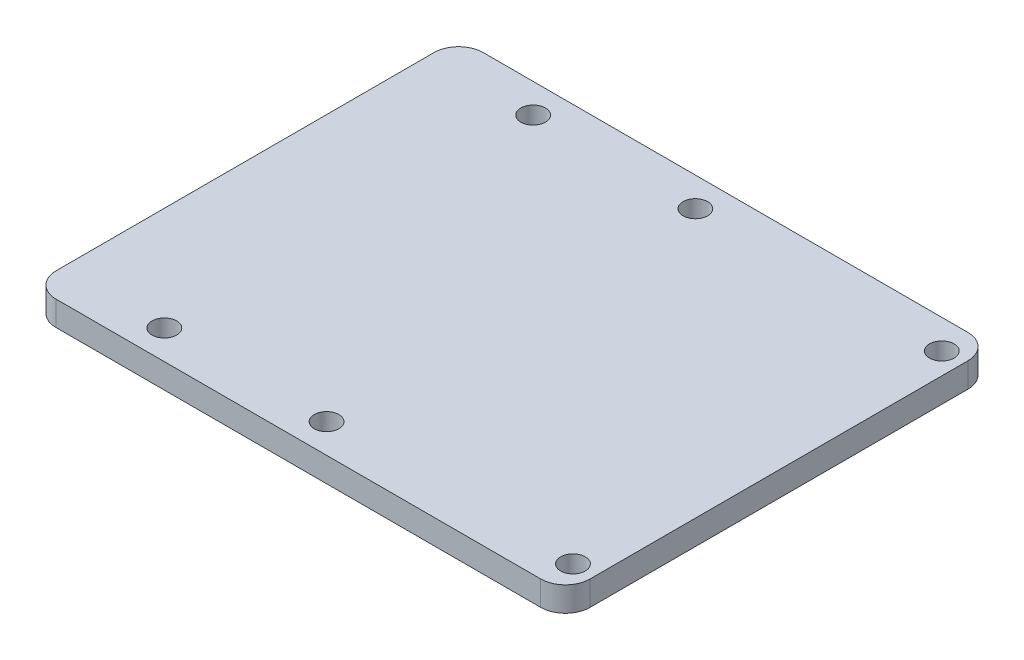
SolidWorks part; units mm, degrees
ref_plane "Front Plane" through (0, 0, 0) normal (0, 0, 1) x (1, 0, 0)
ref_plane "Top Plane" through (0, 0, 0) normal (0, 1, 0) x (1, 0, 0)
ref_plane "Right Plane" through (0, 0, 0) normal (1, 0, 0) x (0, 0, -1)
sketch "Sketch2" plane through (0, 0, 0) normal (0, 1, 0) x (1, 0, 0)
  line L1 (-37.5, -26) -> (27.5, -26)
  line L2 (-37.5, -26) -> (-37.5, 26)
  line L3 (-37.5, 26) -> (27.5, 26)
  line L4 (27.5, -26) -> (27.5, 26)
  line L5 (0, 27) -> (0, -27) construction
  line L6 (-32.5, 0) -> (32.5, 0) construction
  line L7 (-24.875, -22.45) -> (24.875, -22.45)
  line L8 (-24.875, -22.45) -> (-24.875, 22.45)
  line L9 (-24.875, 22.45) -> (24.875, 22.45)
  line L10 (24.875, -22.45) -> (24.875, 22.45)
  line L11 (0, 22.45) -> (0, -22.45) construction
  line L12 (-24.875, 0) -> (24.875, 0) construction
  circle A0 centre (-24.875, 22.45) radius 1.5
  circle A1 centre (24.875, 22.45) radius 1.5
  circle A2 centre (24.875, -22.45) radius 1.5
  circle A3 centre (-24.875, -22.45) radius 1.5
  point P0 (0, 0)
  point P4 (0, 0)
  dimension "D5" = 3
  dimension "D1" = 52
  dimension "D2" = 65
  dimension "D3" = 44.9
  dimension "D4" = 49.75
  dimension "D8" = 3.55
  dimension "D9" = 2.625
  dimension "D6" = 2
  dimension "D7" = 2
extrude "Boss-Extrude1" add sketch "Sketch2" along normal blind 3 contours L1 L4 L3 L2 A3 L8 A0 L9 A1 L10 A2 L7 | A3 L7 A2 L10 A1 L9 A0 L8
fillet "Fillet1" radius 3 4 edges at (27.5, 1.5, 26) (-37.5, 1.5, 26) (27.5, 1.5, -26) (-37.5, 1.5, -26)
sketch "Sketch3" plane through (0, 3, 0) normal (0, 1, 0) x (1, 0, 0)
  circle A0 centre (24.875, 22.45) radius 1.5
  circle A1 centre (-5.125, 22.45) radius 1.5
  circle A2 centre (-5.125, -22.45) radius 1.5
  circle A3 centre (24.875, -22.45) radius 1.5
  dimension "D1" = 3
  dimension "D2" = 2
  dimension "D3" = 2
extrude "Cut-Extrude1" cut sketch "Sketch3" against normal blind 10
